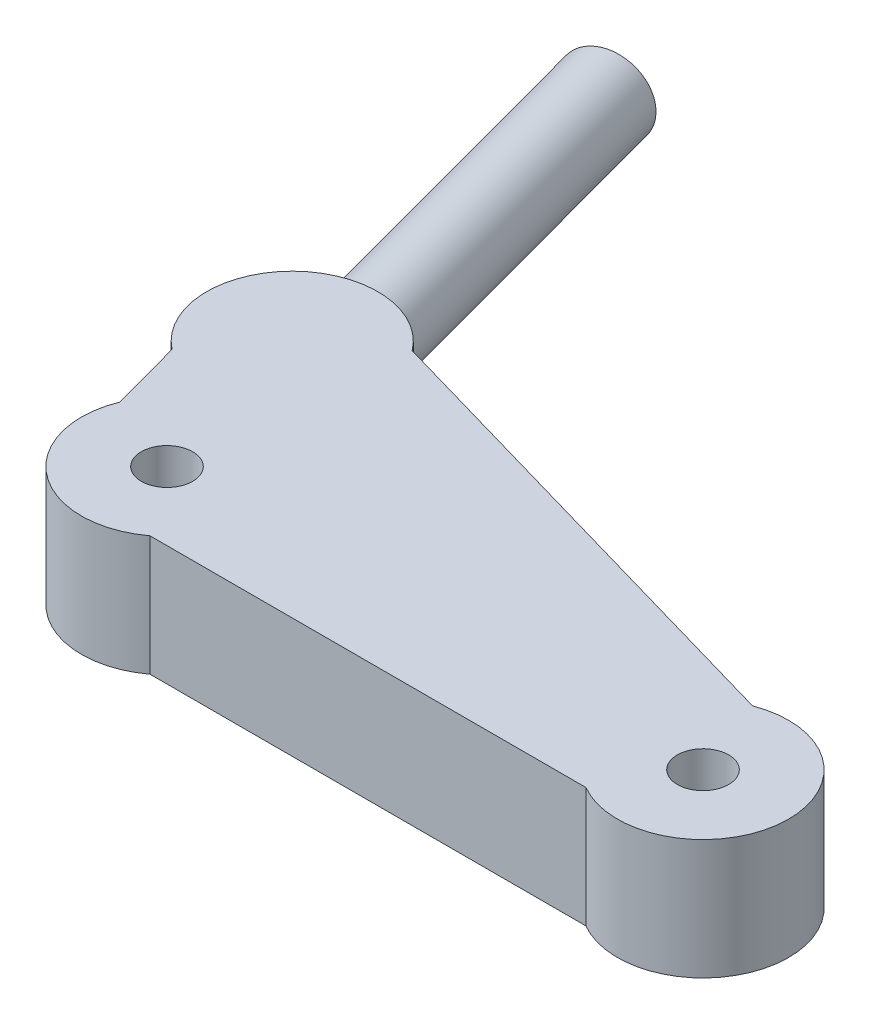
SolidWorks part; units mm, degrees
ref_plane "Alzado" through (0, 0, 0) normal (0, 0, 1) x (1, 0, 0)
ref_plane "Planta" through (0, 0, 0) normal (0, 1, 0) x (1, 0, 0)
ref_plane "Vista lateral" through (0, 0, 0) normal (1, 0, 0) x (0, 0, -1)
sketch "Croquis1" plane through (0, 0, 0) normal (0, 1, 0) x (1, 0, 0)
  line L2 (12.9677, -4) -> (-12.4902, -4)
  line L3 (-15.4918, 0) -> (-17.0569, 5.8238) construction
  line L5 (14.0113, 0.5882) -> (15.4869, 0.319) construction
  line L7 (-21.2636, 6.0647) -> (-20.1338, 1.8607)
  line L8 (15.4869, 0.319) -> (-18.1792, 10) construction
  line L9 (-14.1906, 13.0151) -> (13.7092, 4.9923)
  circle A0 centre (-15.4918, 0) radius 1.5
  circle A2 centre (15.4869, 0.319) radius 1.5
  arc A3 (13.7092, 4.9923) -> (12.9677, -4) centre (15.4869, 0.319) cw
  arc A5 (-14.1906, 13.0151) -> (-21.2636, 6.0647) centre (-18.1792, 10) ccw
  arc A6 (-20.1338, 1.8607) -> (-12.4902, -4) centre (-15.4918, 0) ccw
  dimension "D1" = 3
  dimension "D2" = 4
  dimension "D6" = 5
  dimension "D9" = 3
  dimension "D8" = 10
  dimension "D4" = 4
  dimension "D5" = 30.9804
  dimension "D7" = 15.4902
  dimension "D10" = 10
  dimension "D12" = 4
extrude "Saliente-Extruir1" add sketch "Croquis1" along normal blind 7
ref_plane "Plano2" through (-5.0285, 0, -18.7115) normal (-0.2595, 0, -0.9657) x (-0.9657, 0, 0.2595)
sketch "Croquis3" plane through (-5.0285, 0, -18.7115) normal (-0.2595, 0, -0.9657) x (-0.9657, 0, 0.2595)
  line L0 (19.961, 7) -> (10.3265, 7) construction
  line L1 (14.961, 7) -> (14.961, 0) construction
  circle A0 centre (14.961, 3.5) radius 2.35
  dimension "D1" = 4.7
  dimension "D2" = 3.5
  dimension "D3" = 0
extrude "Saliente-Extruir3" add sketch "Croquis3" along normal blind 21 and the other way blind 3
